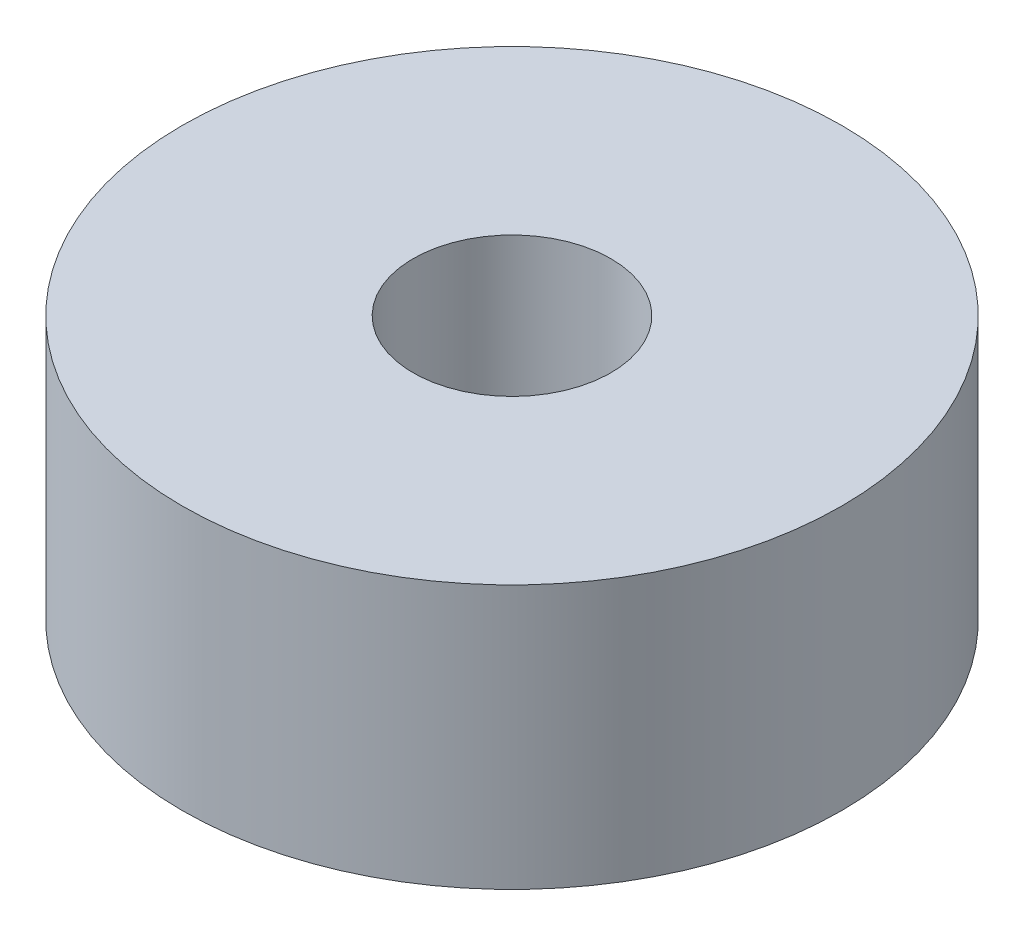
SolidWorks part; units mm, degrees
ref_plane "Front Plane" through (0, 0, 0) normal (0, 0, 1) x (1, 0, 0)
ref_plane "Top Plane" through (0, 0, 0) normal (0, 1, 0) x (1, 0, 0)
ref_plane "Right Plane" through (0, 0, 0) normal (1, 0, 0) x (0, 0, -1)
sketch "Sketch3" plane through (0, 0, 0) normal (0, 1, 0) x (1, 0, 0)
  circle A0 centre (0, 0) radius 50
  dimension "D1" = 100
extrude "Boss-Extrude3" add sketch "Sketch3" along normal blind 40
sketch "Sketch5" plane through (0, 40, 0) normal (0, 1, 0) x (1, 0, 0)
  circle A0 centre (0, 0) radius 15
extrude "Cut-Extrude4" cut sketch "Sketch5" against normal blind 30 and the other way through all
